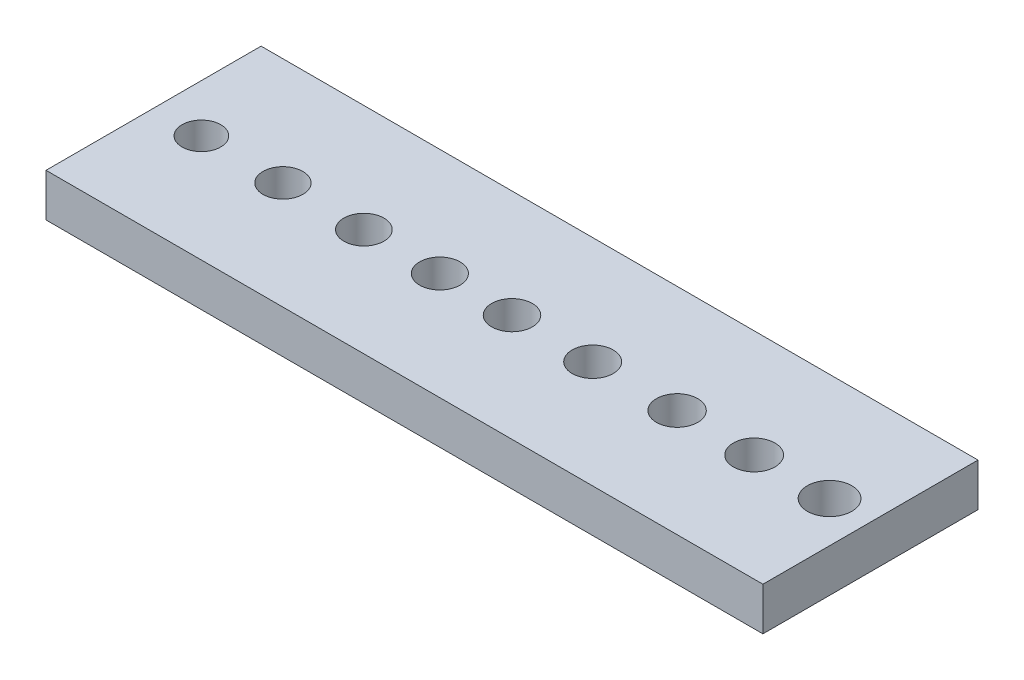
SolidWorks part; units mm, degrees
ref_plane "Alzado" through (0, 0, 0) normal (0, 0, 1) x (1, 0, 0)
ref_plane "Planta" through (0, 0, 0) normal (0, 1, 0) x (1, 0, 0)
ref_plane "Vista lateral" through (0, 0, 0) normal (1, 0, 0) x (0, 0, -1)
sketch "Croquis1" plane through (0, 0, 0) normal (0, 1, 0) x (1, 0, 0)
  line L0 (-25, 0) -> (25, 0) construction
  line L1 (-25, -7.5) -> (25, -7.5)
  line L2 (-25, -7.5) -> (-25, 7.5)
  line L3 (-25, 7.5) -> (25, 7.5)
  line L4 (25, -7.5) -> (25, 7.5)
  line L5 (-25, -7.5) -> (25, 7.5) construction
  line L6 (-25, 7.5) -> (25, -7.5) construction
  circle A0 centre (-21.6627, 0) radius 1.35
  circle A1 centre (-15.9774, 0) radius 1.39
  circle A2 centre (-10.3308, 0) radius 1.4
  circle A3 centre (-5.0323, 0) radius 1.41
  circle A4 centre (0, 0) radius 1.42
  circle A5 centre (5.6266, 0) radius 1.43
  circle A6 centre (11.5164, 0) radius 1.44
  circle A8 centre (16.8874, 0) radius 1.45
  point P0 (0, 0)
  point P22 (8.5051, 0)
  point P23 (4.6452, 0)
  point P26 (-6.9696, 0)
  point P27 (-3.7532, 0)
  point P28 (-2.9085, 0)
  point P29 (-15.5467, 0)
  point P30 (-11.583, 0)
  point P31 (-7.4245, 0)
  point P32 (-21.6627, 0)
  point P33 (-15.9774, 0)
  point P34 (-9.2092, 0)
  point P35 (-10.3308, 0)
  point P36 (-5.0323, 0)
  point P37 (14.4156, 0)
  point P38 (10.1739, 0)
  point P39 (5.6266, 0)
  point P40 (16.5937, 0)
  point P41 (11.2439, 0)
  point P42 (16.8874, 0)
  point P43 (11.6808, 0)
  point P44 (11.5164, 0)
  dimension "D1" = 2.9
  dimension "D2" = 2.7
  dimension "D3" = 2.78
  dimension "D4" = 2.8
  dimension "D5" = 2.82
  dimension "D6" = 2.84
  dimension "D7" = 2.86
  dimension "D8" = 2.88
  dimension "D9" = 50
  dimension "D10" = 15
extrude "Saliente-Extruir1" add sketch "Croquis1" along normal blind 3
hole_wizard "Taladro de margen para M2.51" positions "Croquis2" profile "Croquis3" hole size "M2.5" standard "Ansi Metric"
sketch "Croquis2" plane through (0, 3, 0) normal (0, 1, 0) x (1, 0, 0)
  point P0 (22.1489, 0)
sketch "Croquis3" plane through (22.1489, 3, 0) normal (1, 0, 0) x (0, 0, 1)
  line L0 (0, 0) -> (0, 4.1113)
  line L1 (0, 4.1113) -> (1.55, 3.18)
  line L2 (1.55, 3.18) -> (1.55, 0)
  line L5 (1.55, 0) -> (0, 0)
  line L10 (0, 4.1113) -> (-1.55, 3.18) construction
  line L11 (0, -6.35) -> (0, 107.95) construction
  dimension "Diámetro de taladro" = 3.1
  dimension "Profundidad de taladro" = 3.18
  dimension "Ángulo de perforador" = 118
